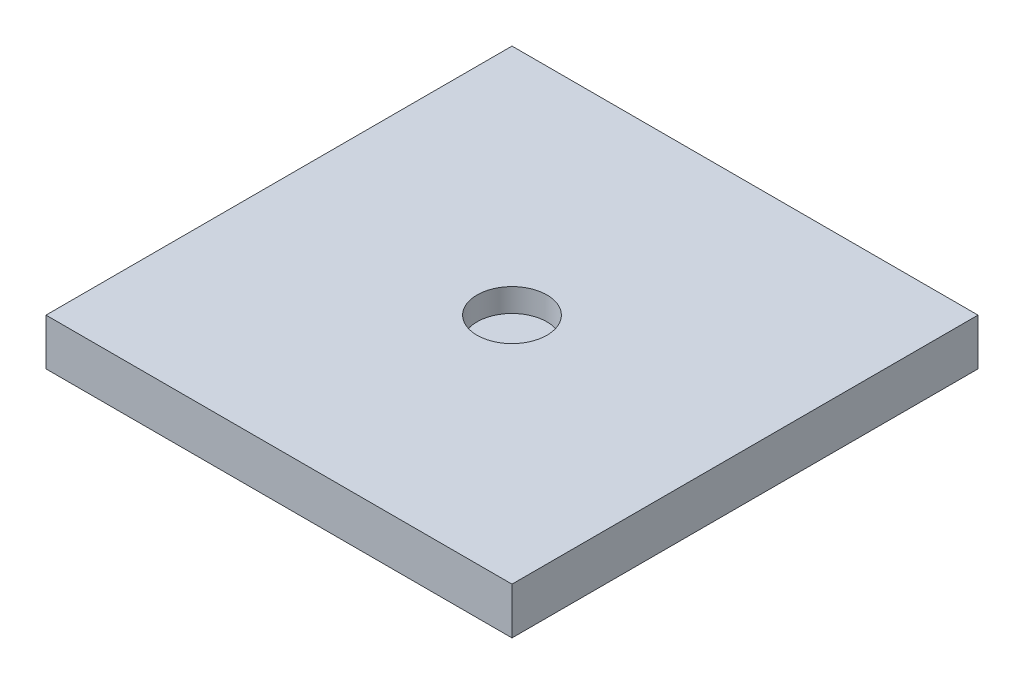
SolidWorks part; units mm, degrees
ref_plane "Front Plane" through (0, 0, 0) normal (0, 0, 1) x (1, 0, 0)
ref_plane "Top Plane" through (0, 0, 0) normal (0, 1, 0) x (1, 0, 0)
ref_plane "Right Plane" through (0, 0, 0) normal (1, 0, 0) x (0, 0, -1)
sketch "Sketch1" plane through (0, 0, 0) normal (0, 1, 0) x (1, 0, 0)
  line L1 (-20, 20) -> (20, 20)
  line L2 (-20, 20) -> (-20, -20)
  line L3 (-20, -20) -> (20, -20)
  line L4 (20, 20) -> (20, -20)
  line L5 (-20, 20) -> (20, -20) construction
  line L6 (-20, -20) -> (20, 20) construction
  point P0 (0, 0)
  dimension "D1" = 40
  dimension "D2" = 40
extrude "Boss-Extrude1" add sketch "Sketch1" along normal blind 4
sketch "Sketch2" plane through (0, 4, 0) normal (0, 1, 0) x (1, 0, 0)
  circle A0 centre (0, 0) radius 3
  dimension "D1" = 6
extrude "Cut-Extrude1" cut sketch "Sketch2" against normal blind 2
